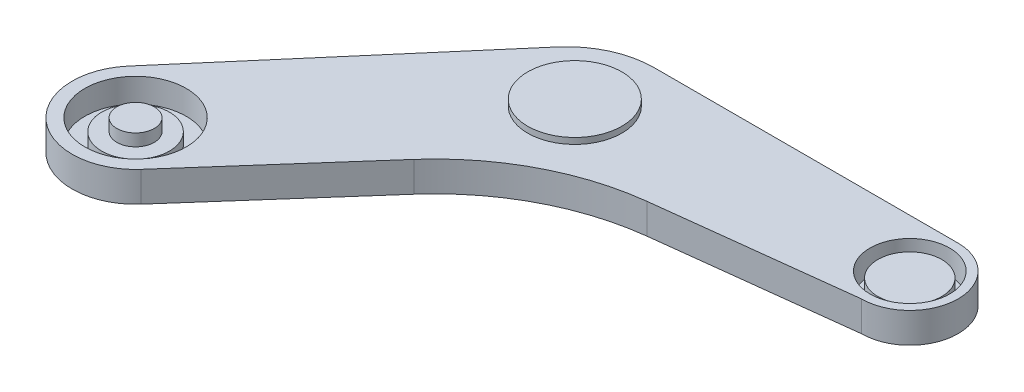
SolidWorks part; units mm, degrees
ref_plane "Front Plane" through (0, 0, 0) normal (0, 0, 1) x (1, 0, 0)
ref_plane "Top Plane" through (0, 0, 0) normal (0, 1, 0) x (1, 0, 0)
ref_plane "Right Plane" through (0, 0, 0) normal (1, 0, 0) x (0, 0, -1)
sketch "Sketch3" plane through (0, 0, 0) normal (0, 1, 0) x (1, 0, 0)
  line L0 (-426.7531, -312.1174) -> (-99.3439, 70.1068)
  line L1 (10.7784, 120.7772) -> (514.0598, 120.7772)
  line L2 (-268.225, -449.8369) -> (-56.6839, -209.732)
  line L3 (514.0598, -39.2228) -> (196.2913, -76.9476)
  circle A0 centre (0, 0) radius 120
  arc A1 (-426.7531, -312.1174) -> (-268.225, -449.8369) centre (-347.0094, -380.425) ccw
  arc A2 (514.0598, -39.2228) -> (514.0598, 120.7772) centre (514.0598, 40.7772) ccw
  arc A3 (-99.3439, 70.1068) -> (10.7784, 120.7772) centre (10.7784, -24.2228) cw
  arc A4 (196.2913, -76.9476) -> (-56.6839, -209.732) centre (243.4473, -474.1582) ccw
  point P15 (-55.9402, 120.7772)
  dimension "D1" = 210
  dimension "D2" = 240
  dimension "D3" = 160
  dimension "D6" = 145
  dimension "D7" = 800
  dimension "D4" = 570
  dimension "D5" = 570
  dimension "D8" = 320
  dimension "D9" = 320
extrude "Boss-Extrude2" add sketch "Sketch3" along normal blind 50 contours A4 L3 A2 L1 A3 A0 L0 A1 L2 | A3 A0
sketch "Sketch4" plane through (0, 50, 0) normal (0, 1, 0) x (1, 0, 0)
  circle A0 centre (-347.0094, -380.425) radius 84
  circle A1 centre (-347.0094, -380.425) radius 56
  circle A2 centre (-347.0094, -380.425) radius 31
  circle A3 centre (514.0598, 40.7772) radius 66
  circle A4 centre (514.0598, 40.7772) radius 53
extrude "Cut-Extrude1" cut sketch "Sketch4" against normal blind 40 contours A0
sketch "Sketch5" plane through (0, 50, 0) normal (0, 1, 0) x (1, 0, 0)
  circle A0 centre (514.0598, 40.7772) radius 66
extrude "Cut-Extrude2" cut sketch "Sketch5" against normal blind 40
sketch "Sketch6" plane through (0, 10, 0) normal (0, 1, 0) x (1, 0, 0)
  circle A0 centre (-347.0094, -380.425) radius 56
extrude "Boss-Extrude3" add sketch "Sketch6" along normal blind 20
sketch "Sketch7" plane through (0, 30, 0) normal (0, 1, 0) x (1, 0, 0)
  circle A0 centre (-347.0094, -380.425) radius 31
extrude "Boss-Extrude4" add sketch "Sketch7" along normal blind 20
sketch "Sketch8" plane through (0, 10, 0) normal (0, 1, 0) x (1, 0, 0)
  circle A0 centre (514.0598, 40.7772) radius 53
extrude "Boss-Extrude5" add sketch "Sketch8" along normal blind 30
sketch "Sketch9" plane through (0, 0, 0) normal (0, -1, 0) x (1, 0, 0)
  circle A0 centre (0, 0) radius 81.1188
extrude "Boss-Extrude6" add sketch "Sketch9" along normal blind 10
sketch "Sketch10" plane through (0, 50, 0) normal (0, 1, 0) x (1, 0, 0)
  circle A0 centre (0, 0) radius 77.9949
extrude "Boss-Extrude7" add sketch "Sketch10" along normal blind 10
